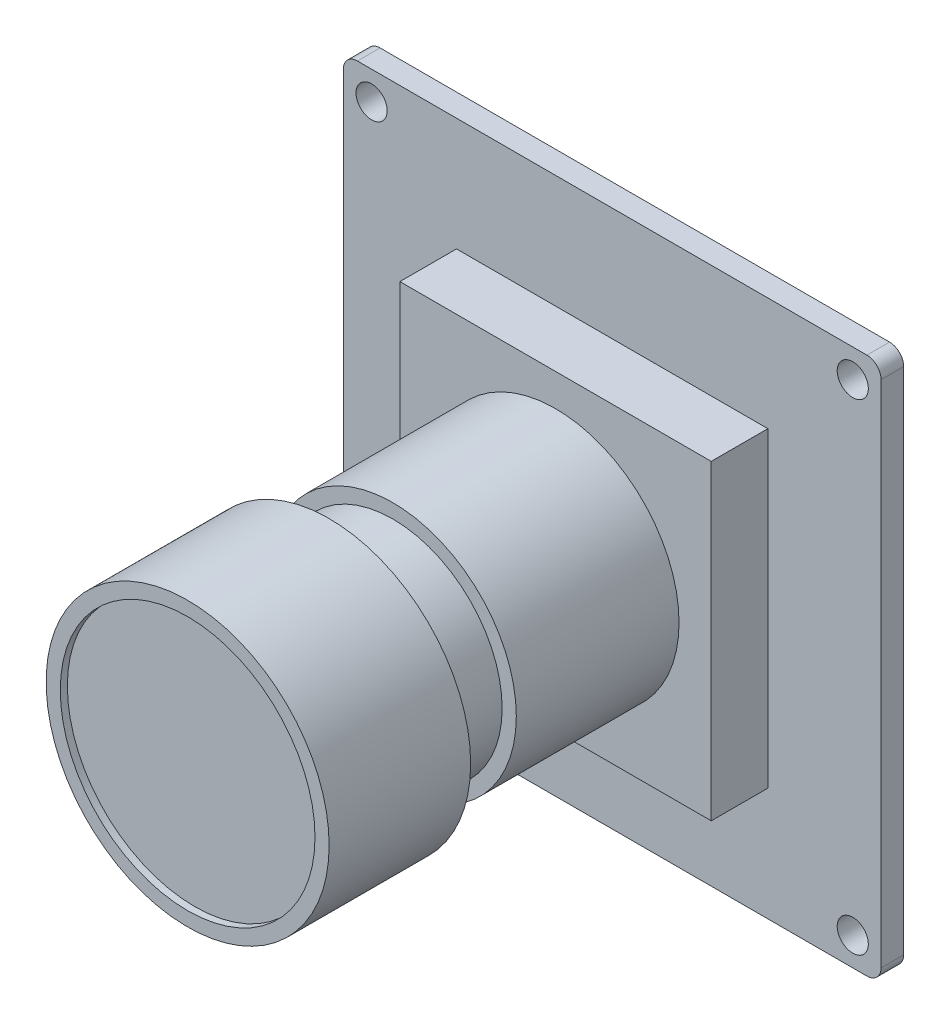
SolidWorks part; units mm, degrees
ref_plane "정면" through (0, 0, 0) normal (0, 0, 1) x (1, 0, 0)
ref_plane "윗면" through (0, 0, 0) normal (0, 1, 0) x (1, 0, 0)
ref_plane "우측면" through (0, 0, 0) normal (1, 0, 0) x (0, 0, -1)
sketch "스케치1" plane through (0, 0, 0) normal (0, 0, 1) x (1, 0, 0)
  line L0 (19, 19) -> (-19, -19) construction
  line L1 (-19, 19) -> (19, 19)
  line L2 (-19, 19) -> (-19, -19)
  line L3 (-19, -19) -> (19, -19)
  line L4 (19, 19) -> (19, -19)
  dimension "D1" = 38
  dimension "D2" = 38
extrude "보스-돌출1" add sketch "스케치1" along normal blind 1.6
sketch "스케치2" plane through (0, 0, 1.6) normal (0, 0, 1) x (1, 0, 0)
  line L0 (-17, 17) -> (17, 17) construction
  line L1 (17, 17) -> (17, -17) construction
  line L2 (17, -17) -> (-17, -17) construction
  line L3 (-17, -17) -> (-17, 17) construction
  line L4 (17, 17) -> (-17, -17) construction
  circle A0 centre (-17, 17) radius 1.1
  circle A1 centre (17, -17) radius 1.1
  circle A2 centre (17, 17) radius 1.1
  circle A3 centre (-17, -17) radius 1.1
  dimension "D1" = 2.2
  dimension "D2" = 34
extrude "컷-돌출1" cut sketch "스케치2" against normal through all
fillet "필렛1" radius 1 4 edges at (-19, -19, 0.8) (19, -19, 0.8) (19, 19, 0.8) (-19, 19, 0.8)
sketch "스케치3" plane through (0, 0, 1.6) normal (0, 0, 1) x (1, 0, 0)
  line L0 (-11, 11) -> (11, -11) construction
  line L1 (-11, 11) -> (11, 11)
  line L2 (-11, 11) -> (-11, -11)
  line L3 (-11, -11) -> (11, -11)
  line L4 (11, 11) -> (11, -11)
  dimension "D1" = 22
  dimension "D2" = 22
extrude "보스-돌출2" add sketch "스케치3" along normal blind 4
sketch "스케치4" plane through (0, 0, 1.6) normal (0, 0, 1) x (1, 0, 0)
  circle A0 centre (0, 0) radius 8.725
  dimension "D1" = 17.45
extrude "보스-돌출3" add sketch "스케치4" along normal blind 15.5
sketch "스케치5" plane through (0, 0, 1.6) normal (0, 0, 1) x (1, 0, 0)
  circle A0 centre (0, 0) radius 7.725
  dimension "D1" = 15.45
extrude "보스-돌출4" add sketch "스케치5" along normal blind 30
sketch "스케치6" plane through (0, 0, 31.6) normal (0, 0, 1) x (1, 0, 0)
  circle A0 centre (0, 0) radius 10
  dimension "D1" = 20
extrude "보스-돌출5" add sketch "스케치6" against normal blind 10
sketch "스케치7" plane through (0, 0, 31.6) normal (0, 0, 1) x (1, 0, 0)
  circle A0 centre (0, 0) radius 9
  dimension "D1" = 18
extrude "컷-돌출3" cut sketch "스케치7" against normal blind 0.5
